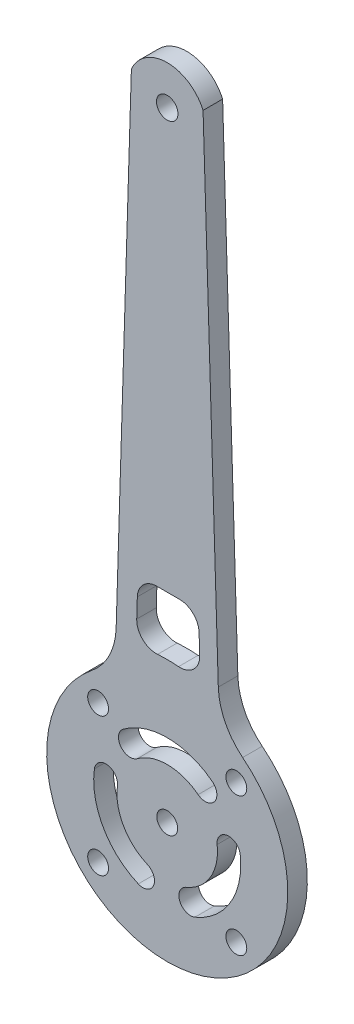
SolidWorks part; units mm, degrees
material "Thornel Mat VMA"
ref_plane "前视基准面" through (0, 0, 0) normal (0, 0, 1) x (1, 0, 0)
ref_plane "上视基准面" through (0, 0, 0) normal (0, 1, 0) x (1, 0, 0)
ref_plane "右视基准面" through (0, 0, 0) normal (1, 0, 0) x (0, 0, -1)
other "Configuration Table"
sketch "草图1" plane through (0, 0, 0) normal (0, 0, 1) x (1, 0, 0)
  line L0 (-5.5, 2.3979) -> (-8, -78.3192)
  line L1 (5.5, 2.3979) -> (8, -78.3192)
  line L2 (0, 0) -> (0, -60.2528) construction
  line L8 (0, -62.5) -> (0, -95) construction
  line L13 (-4.499, -64.3906) -> (-4.7926, -73.87)
  line L16 (4.7992, -64.3906) -> (5.095, -73.9409)
  line L17 (-4.499, -64.3906) -> (4.7992, -64.3906)
  line L18 (10.6066, -84.3934) -> (0, -95) construction
  line L19 (0, -95) -> (-7.5835, -95) construction
  arc A0 (5.5, 2.3979) -> (-5.5, 2.3979) centre (0, 0) ccw
  arc A1 (-8, -78.3192) -> (8, -78.3192) centre (0, -95) ccw
  circle A2 centre (0, 0) radius 1.65
  circle A3 centre (0, -95) radius 9.5 construction
  circle A4 centre (0, -95) radius 8 construction
  circle A9 centre (0, -95) radius 1.6
  arc A12 (5.095, -73.9409) -> (-4.7926, -73.87) centre (0, -95) ccw
  circle A13 centre (0, -95) radius 15 construction
  circle A14 centre (10.6066, -84.3934) radius 1.6
  circle A15 centre (10.6066, -105.6066) radius 1.6
  circle A16 centre (-10.6066, -105.6066) radius 1.6
  circle A17 centre (-10.6066, -84.3934) radius 1.6
  arc A18 (-5.6926, -87.3945) -> (5.8367, -87.5045) centre (0, -95) cw construction
  arc A19 (6.9331, -86.0964) -> (-6.762, -85.9658) centre (0, -95) ccw
  arc A20 (4.7403, -88.9125) -> (-4.6233, -88.8232) centre (0, -95) ccw
  arc A21 (4.7403, -88.9125) -> (6.9331, -86.0964) centre (5.8367, -87.5045) ccw
  arc A22 (-6.762, -85.9658) -> (-4.6233, -88.8232) centre (-5.6926, -87.3945) ccw
  arc A23 (9.4329, -93.8728) -> (3.573, -103.8025) centre (0, -95) cw construction
  arc A28 (4.2442, -105.456) -> (11.2048, -93.661) centre (0, -95) ccw
  arc A29 (2.9018, -102.149) -> (7.6609, -94.0845) centre (0, -95) ccw
  arc A30 (2.9018, -102.149) -> (4.2442, -105.456) centre (3.573, -103.8025) ccw
  arc A31 (11.2048, -93.661) -> (7.6609, -94.0845) centre (9.4329, -93.8728) ccw
  arc A32 (-3.7402, -103.7327) -> (-9.4097, -93.693) centre (0, -95) cw construction
  arc A33 (-11.1773, -93.4475) -> (-4.4428, -105.3732) centre (0, -95) ccw
  arc A34 (-7.6421, -93.9386) -> (-3.0376, -102.0923) centre (0, -95) ccw
  arc A35 (-7.6421, -93.9386) -> (-11.1773, -93.4475) centre (-9.4097, -93.693) ccw
  arc A36 (-4.4428, -105.3732) -> (-3.0376, -102.0923) centre (-3.7402, -103.7327) ccw
  point P13 (0.0906, -85.5004)
  point P49 (0, -95)
  point P53 (8.1816, -99.8283)
  point P60 (-8.2722, -99.6713)
  point P65 (0, -95)
  dimension "D1" = 12
  dimension "D2" = 37
  dimension "D5" = 3.3
  dimension "D6" = 19
  dimension "D7" = 16
  dimension "D8" = 3
  dimension "D4" = 3.2
  dimension "D11" = 30
  dimension "D12" = 3.2
  dimension "D3" = 95
  dimension "D9" = 16
  dimension "D10" = 11
  dimension "D13" = 45
  dimension "D14" = 4
extrude "凸台-拉伸1" add sketch "草图1" along normal blind 3
fillet "圆角2" radius 10 2 edges at (8, -78.3192, 1.5) (-8, -78.3192, 1.5)
fillet "圆角3" radius 3 4 edges at (5.095, -73.9409, 1.5) (-4.7926, -73.87, 1.5) (-4.499, -64.3906, 1.5) (4.7992, -64.3906, 1.5)
